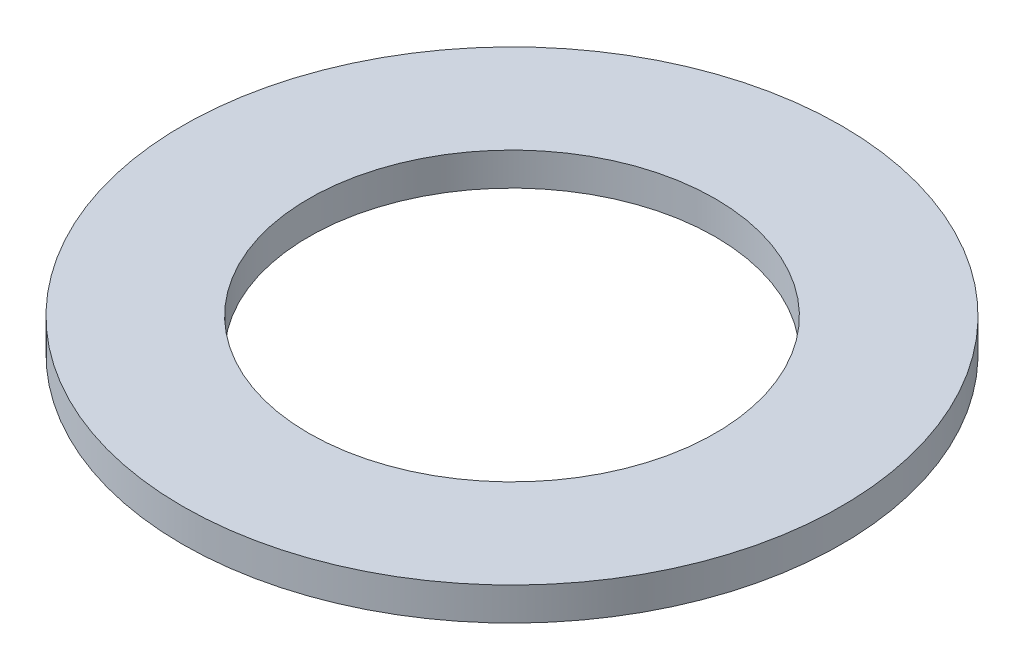
SolidWorks part; units mm, degrees
ref_plane "Front Plane" through (0, 0, 0) normal (0, 0, 1) x (1, 0, 0)
ref_plane "Top Plane" through (0, 0, 0) normal (0, 1, 0) x (1, 0, 0)
ref_plane "Right Plane" through (0, 0, 0) normal (1, 0, 0) x (0, 0, -1)
sketch "Sketch1" plane through (0, 0, 0) normal (0, 1, 0) x (1, 0, 0)
  circle A0 centre (0, 0) radius 9.25
  circle A1 centre (0, 0) radius 15
  dimension "D1" = 30
  dimension "D2" = 18.5
extrude "Boss-Extrude1" add sketch "Sketch1" along normal mid plane 1.5
